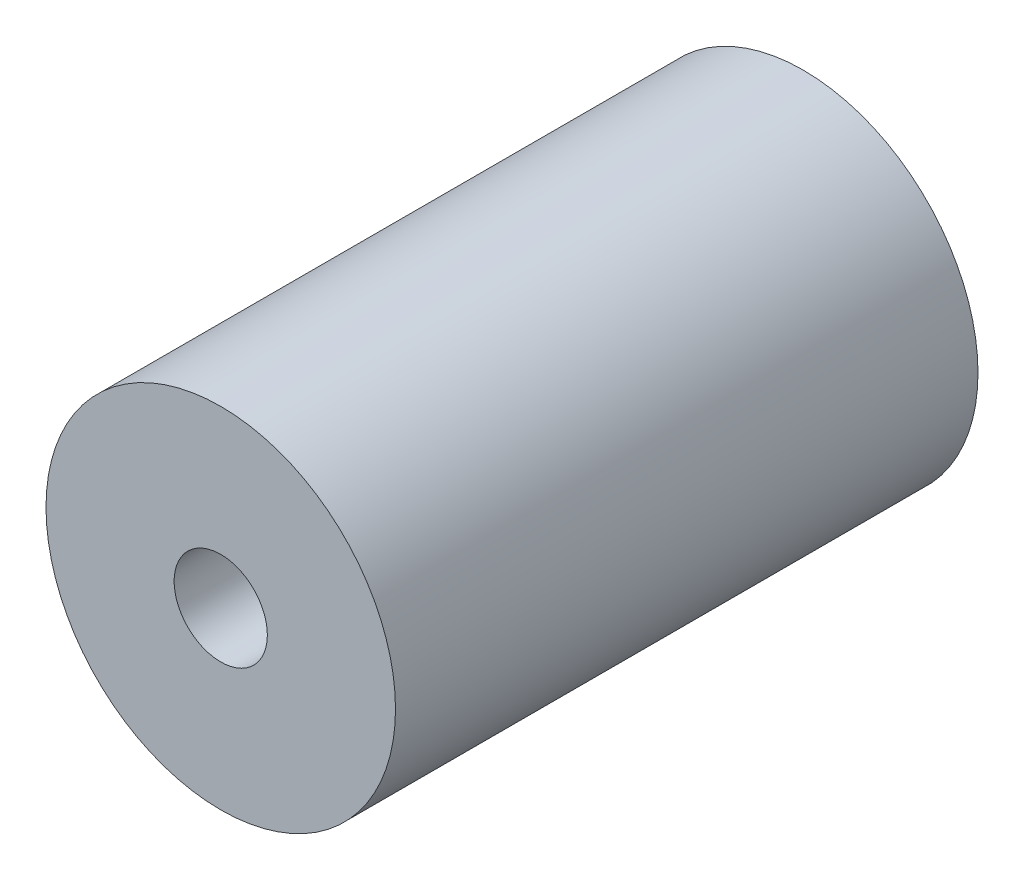
SolidWorks part; units mm, degrees
ref_plane "Front Plane" through (0, 0, 0) normal (0, 0, 1) x (1, 0, 0)
ref_plane "Top Plane" through (0, 0, 0) normal (0, 1, 0) x (1, 0, 0)
ref_plane "Right Plane" through (0, 0, 0) normal (1, 0, 0) x (0, 0, -1)
sketch "Sketch1" plane through (0, 0, 0) normal (0, 0, 1) x (1, 0, 0)
  circle A0 centre (0, 0) radius 3
  circle A1 centre (0, 0) radius 0.8
extrude "Boss-Extrude1" add sketch "Sketch1" along normal blind 10
